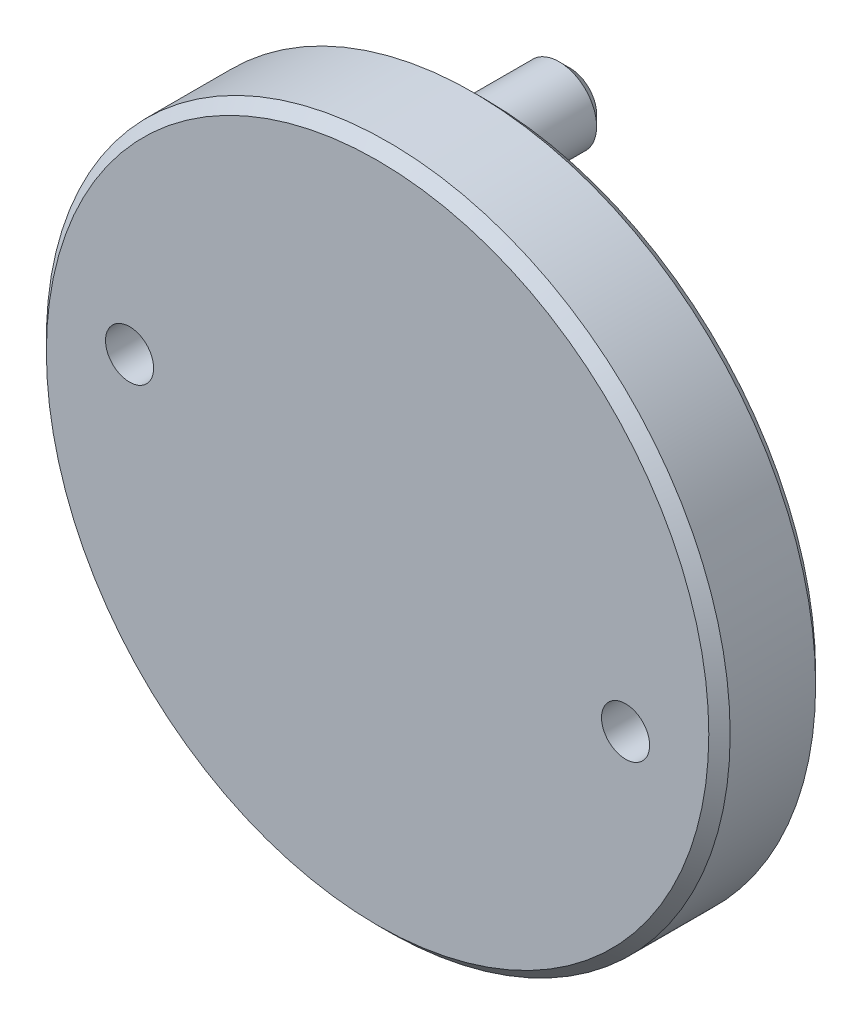
SolidWorks part; units mm, degrees
material "AISI 1010 钢，热轧条材"
ref_plane "前视基准面" through (0, 0, 0) normal (0, 0, 1) x (1, 0, 0)
ref_plane "上视基准面" through (0, 0, 0) normal (0, 1, 0) x (1, 0, 0)
ref_plane "右视基准面" through (0, 0, 0) normal (1, 0, 0) x (0, 0, -1)
sketch "草图1" plane through (0, 0, 0) normal (0, 0, 1) x (1, 0, 0)
  line L0 (-11.5, 18.1659) -> (-7.5647, 29.6029)
  line L1 (0, 0) -> (0, 39.4904) construction
  line L2 (11.5, 18.1659) -> (7.5647, 29.6029)
  line L3 (21.4821, 0.8763) -> (29.4192, -8.2502)
  line L4 (9.9821, -19.0422) -> (21.8545, -21.3527)
  line L5 (-9.9821, -19.0422) -> (-21.8545, -21.3527)
  line L6 (-21.4821, 0.8763) -> (-29.4192, -8.2502)
  arc A0 (-11.5, 18.1659) -> (-21.4821, 0.8763) centre (0, 0) ccw
  circle A1 centre (0, 0) radius 27 construction
  arc A2 (7.5647, 29.6029) -> (-7.5647, 29.6029) centre (0, 27) ccw
  arc A3 (21.8545, -21.3527) -> (29.4192, -8.2502) centre (23.3827, -13.5) ccw
  arc A4 (-29.4192, -8.2502) -> (-21.8545, -21.3527) centre (-23.3827, -13.5) ccw
  arc A5 (21.4821, 0.8763) -> (11.5, 18.1659) centre (0, 0) ccw
  arc A6 (-9.9821, -19.0422) -> (9.9821, -19.0422) centre (0, 0) ccw
  circle A7 centre (0, 27) radius 3.5
  circle A8 centre (23.3827, -13.5) radius 3.5
  circle A9 centre (-23.3827, -13.5) radius 3.5
  point P23 (0, 0)
  point P28 (0, 0)
  dimension "D1" = 43
  dimension "D2" = 54
  dimension "D3" = 16
  dimension "D4" = 3
  dimension "D6" = 7
  dimension "D7" = 3
  dimension "D5" = 23
extrude "凸台-拉伸1" add sketch "草图1" along normal blind 5
fillet "圆角1" radius 10 6 edges at (-9.9821, -19.0422, 2.5) (9.9821, -19.0422, 2.5) (21.4821, 0.8763, 2.5) (11.5, 18.1659, 2.5) (-21.4821, 0.8763, 2.5) (-11.5, 18.1659, 2.5)
sketch "草图2" plane through (0, 0, 5) normal (0, 0, 1) x (1, 0, 0)
  circle A0 centre (0, 0) radius 18
  dimension "D1" = 36
extrude "凸台-拉伸2" add sketch "草图2" along normal blind 3
sketch "草图3" plane through (0, 0, 8) normal (0, 0, 1) x (1, 0, 0)
  circle A0 centre (0, 0) radius 14
  dimension "D1" = 28
extrude "切除-拉伸1" cut sketch "草图3" against normal blind 32
sketch "草图4" plane through (0, 0, 0) normal (0, 0, -1) x (-1, 0, 0)
  circle A0 centre (0, 0) radius 16.75
  dimension "D1" = 33.5
extrude "切除-拉伸2" cut sketch "草图4" against normal blind 3
chamfer "倒角1" distance 0.5 angle 45 1 edges at (18, 0, 8)
sketch "草图5" plane through (0, 0, 8) normal (0, 0, 1) x (1, 0, 0)
  circle A0 centre (0, 0) radius 32
  dimension "D1" = 64
extrude "凸台-拉伸3" add sketch "草图5" along normal blind 10 separate body
sketch "草图6" plane through (0, 0, 8) normal (0, 0, -1) x (-1, 0, 0)
  circle A2 centre (0, 27) radius 3.5
  circle A3 centre (0, 27) radius 3.5
  circle A6 centre (0, 0) radius 14
  circle A7 centre (0, 0) radius 14
  dimension "D1" = 0
  dimension "D2" = 0
extrude "凸台-拉伸4" add sketch "草图6" along normal blind 8
sketch "草图7" plane through (0, 0, 0) normal (1, 0, 0) x (0, 0, -1)
  line L1 (-11.9622, 46.1604) -> (9.9123, 46.1604)
  line L2 (-11.9622, 46.1604) -> (-11.9622, -27.8179)
  line L3 (-11.9622, -27.8179) -> (9.9123, -27.8179)
  line L4 (9.9123, 46.1604) -> (9.9123, -27.8179)
extrude "切除-拉伸3" cut sketch "草图7" against normal mid plane 125
chamfer "倒角2" distance 1 angle 45 2 edges at (-14, 0, 0) (-3.5, 27, 0)
chamfer "倒角3" distance 1 angle 45 2 edges at (32, 0, 18) (32, 0, 8)
sketch "草图8" plane through (0, 0, 8) normal (0, 0, -1) x (-1, 0, 0)
  line L0 (0, 0) -> (0, -50000) construction
  line L1 (0, 0) -> (7821.7233, -49384.417) construction
  line L2 (-23.5627, -1.4539) -> (7798.5126, -49388.0932) construction
  line L3 (23.2107, 3.6762) -> (7844.9339, -49380.7408) construction
  line L5 (-23.2107, -3.6762) -> (7798.5126, -49388.0932) construction
  circle A0 centre (0, 0) radius 23.5 construction
  circle A1 centre (-23.2107, -3.6762) radius 2.25
  circle A2 centre (23.2107, 3.6762) radius 2.25
  dimension "D2" = 47
  dimension "D5" = 4.5
  dimension "D1" = 9
  dimension "D3" = 23.5
  dimension "D4" = 23.5
extrude "切除-拉伸4" cut sketch "草图8" against normal blind 125
sketch "草图9" plane through (0, 0, 8) normal (0, 0, -1) x (-1, 0, 0)
  circle A0 centre (-23.2107, -3.6762) radius 4
  circle A1 centre (23.2107, 3.6762) radius 4
  dimension "D1" = 8
extrude "切除-拉伸5" cut sketch "草图9" against normal blind 4
